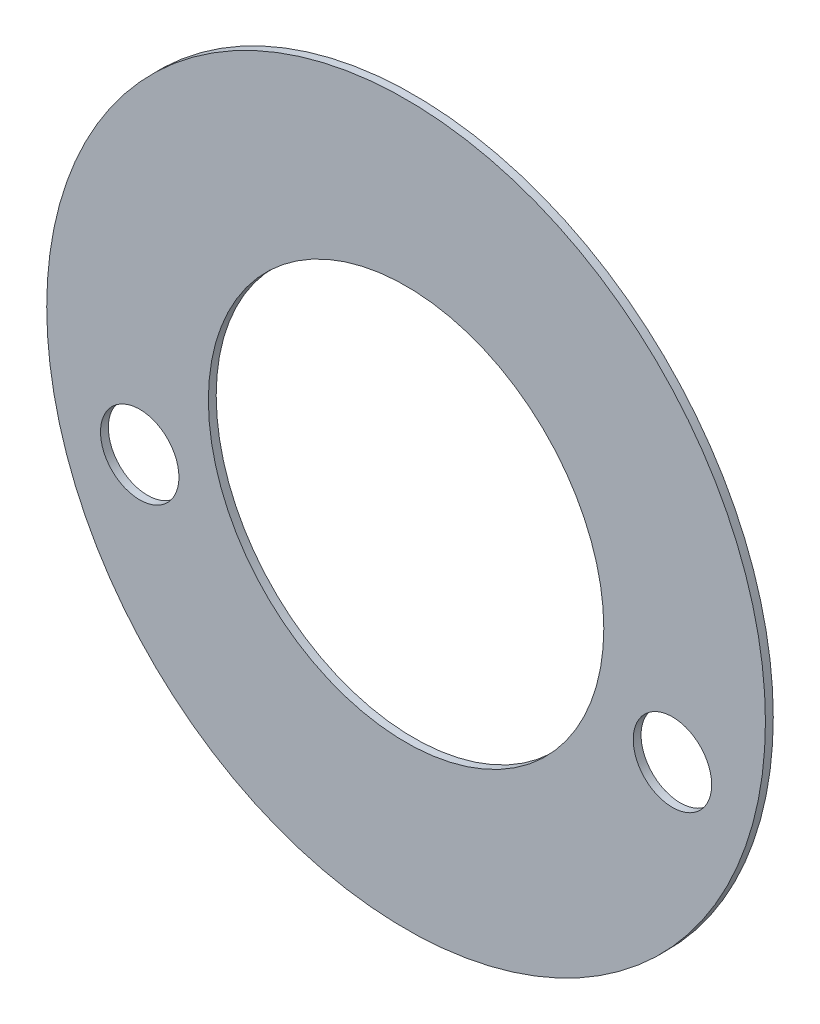
SolidWorks part; units mm, degrees
ref_plane "Ön Düzlem" through (0, 0, 0) normal (0, 0, 1) x (1, 0, 0)
ref_plane "Üst Düzlem" through (0, 0, 0) normal (0, 1, 0) x (1, 0, 0)
ref_plane "Sağ Düzlem" through (0, 0, 0) normal (1, 0, 0) x (0, 0, -1)
sketch "Çizim1" plane through (0, 0, 0) normal (0, 0, 1) x (1, 0, 0)
  circle A0 centre (0, 0) radius 22.9
  circle A1 centre (0, 0) radius 12.6
  circle A2 centre (-16.9735, -5.1926) radius 2.5
  circle A4 centre (16.9735, -5.1926) radius 2.5
  point P6 (17.3716, -3.6455)
  point P7 (0, 0)
  dimension "D1" = 45.8
  dimension "D2" = 25.2
  dimension "D3" = 5
  dimension "D4" = 2.65
  dimension "D5" = 5
  dimension "D6" = 2.65
  dimension "D7" = 145.98
extrude "Yükseklik-Ekstrüzyon1" add sketch "Çizim1" along normal blind 0.5
